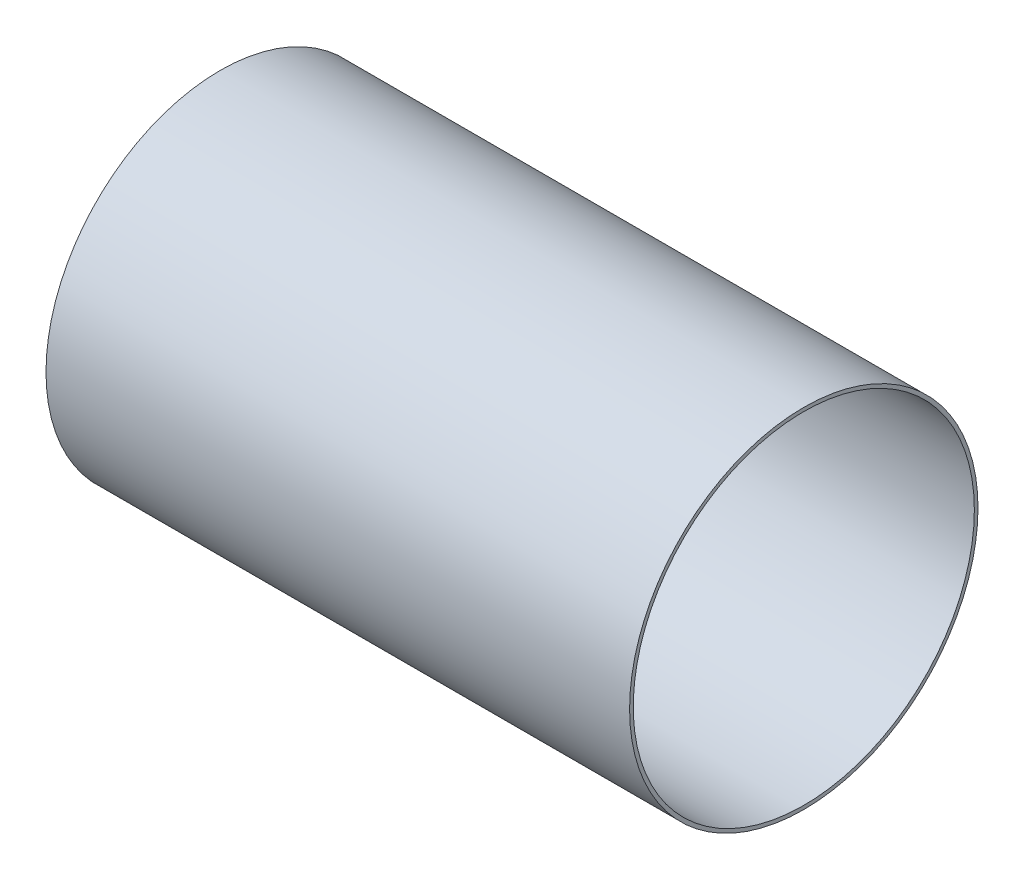
SolidWorks part; units mm, degrees
ref_plane "Front Plane" through (0, 0, 0) normal (1, 0, 0) x (0, 1, 0)
ref_plane "Top Plane" through (0, 0, 0) normal (0, 0, 1) x (0, 1, 0)
ref_plane "Right Plane" through (0, 0, 0) normal (0, 1, 0) x (-1, 0, 0)
sketch "Sketch1" plane through (0, 0, 0) normal (1, 0, 0) x (0, 1, 0)
  circle A0 centre (0, 0) radius 75.819
  circle A1 centre (0, 0) radius 74.2315
  dimension "D1" = 151.638
  dimension "D2" = 148.463
extrude "Boss-Extrude1" add sketch "Sketch1" along normal blind 254
